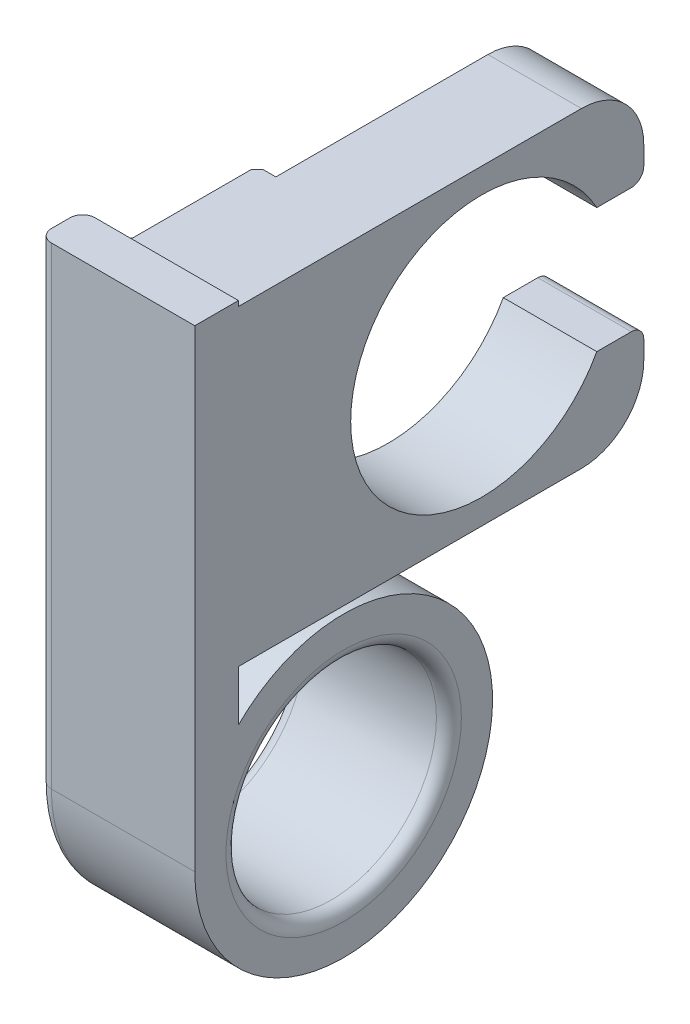
SolidWorks part; units mm, degrees
ref_plane "Front Plane" through (0, 0, 0) normal (0, 0, 1) x (1, 0, 0)
ref_plane "Top Plane" through (0, 0, 0) normal (0, 1, 0) x (1, 0, 0)
ref_plane "Right Plane" through (0, 0, 0) normal (1, 0, 0) x (0, 0, -1)
sketch "Sketch1" plane through (0, 0, 0) normal (1, 0, 0) x (0, 0, -1)
  circle A0 centre (0, 0) radius 16.875
  circle A1 centre (0, 0) radius 23.875
  dimension "D1" = 33.75
  dimension "D2" = 7
extrude "Boss-Extrude1" add sketch "Sketch1" along normal blind 25 contours A1 | A0
sketch "Sketch2" plane through (0, 0, 0) normal (0, 1, 0) x (1, 0, 0)
  line L0 (25, -23.875) -> (25, 23.875) construction
  line L1 (0, -23.875) -> (25, -23.875)
  line L2 (0, -23.875) -> (0, -16.875)
  line L3 (0, -16.875) -> (25, -16.875)
  line L4 (25, -23.875) -> (25, -16.875)
  line L5 (25, -16.875) -> (25, 16.875) construction
extrude "Boss-Extrude2" add sketch "Sketch2" along normal blind 75.83
sketch "Sketch4" plane through (25, 0, 0) normal (-1, 0, 0) x (0, 0, 1)
  line L0 (-22.125, 50) -> (23.875, 50) construction
  line L1 (23.875, 75.83) -> (23.875, 0) construction
  line L2 (-22.125, 29) -> (-22.125, 71)
  line L3 (-22.125, 25) -> (-22.125, 75)
  line L4 (-22.125, 75) -> (23.875, 75)
  line L5 (23.875, 75) -> (23.875, 25)
  line L6 (23.875, 25) -> (-22.125, 25)
  line L7 (-22.125, 75) -> (-48.125, 75)
  line L8 (-48.125, 75) -> (-48.125, 25)
  line L9 (-48.125, 25) -> (-22.125, 25)
  line L10 (-48.125, 60) -> (-40.5912, 60)
  line L11 (-48.125, 40) -> (-40.5912, 40)
  circle A0 centre (-22.125, 50) radius 11
  circle A1 centre (-22.125, 50) radius 21
  arc A2 (16.875, 16.8893) -> (23.875, 0) centre (0, 0) ccw construction
  point P13 (-22.125, 50)
  line M22 (16.875, 16.8893) -> (16.875, 75.83)
  dimension "D1" = 22
  dimension "D2" = 42
  dimension "D3" = 50
  dimension "D4" = 46
  dimension "D5" = 50
  dimension "D6" = 26
  dimension "D7" = 20
extrude "Boss-Extrude3" add sketch "Sketch4" along normal blind 15 contours A1 L3 L4 M22 | L3 A1 L6 M22 | L3 A1 L10 L8 L7 | L11 A1 L3 L9 L8
fillet "Fillet1" radius 10 2 edges at (17.5, 25, -48.125) (17.5, 75, -48.125)
fillet "Fillet2" radius 2 5 edges at (25, 0, -16.875) (0, 37.915, 23.875) (0, 46.3597, 16.875) (0, -9.1413, -22.0557) (0, 0, -16.875)
fillet "Fillet3" radius 2 2 edges at (17.5, 40, -48.125) (17.5, 60, -48.125)
sketch "Sketch5" plane through (10, 0, 0) normal (-1, 0, 0) x (0, 0, 1)
  line L0 (16.875, 25) -> (-38.125, 25) construction
  line L1 (16.875, 25) -> (-4.125, 25)
  line L2 (16.875, 25) -> (16.875, 75)
  line L3 (16.875, 75) -> (-4.125, 75)
  line L4 (-4.125, 25) -> (-4.125, 75)
  line L5 (-38.125, 75) -> (16.875, 75) construction
  line L6 (16.875, 25) -> (16.875, 75) construction
  arc A0 (-40.5912, 40) -> (-40.5912, 60) centre (-22.125, 50) ccw construction
  dimension "D1" = 18
extrude "Boss-Extrude4" add sketch "Sketch5" along normal blind 3
chamfer "Chamfer1" distance 1 angle 45 2 edges at (7, 50, 16.875) (7, 50, -4.125)
